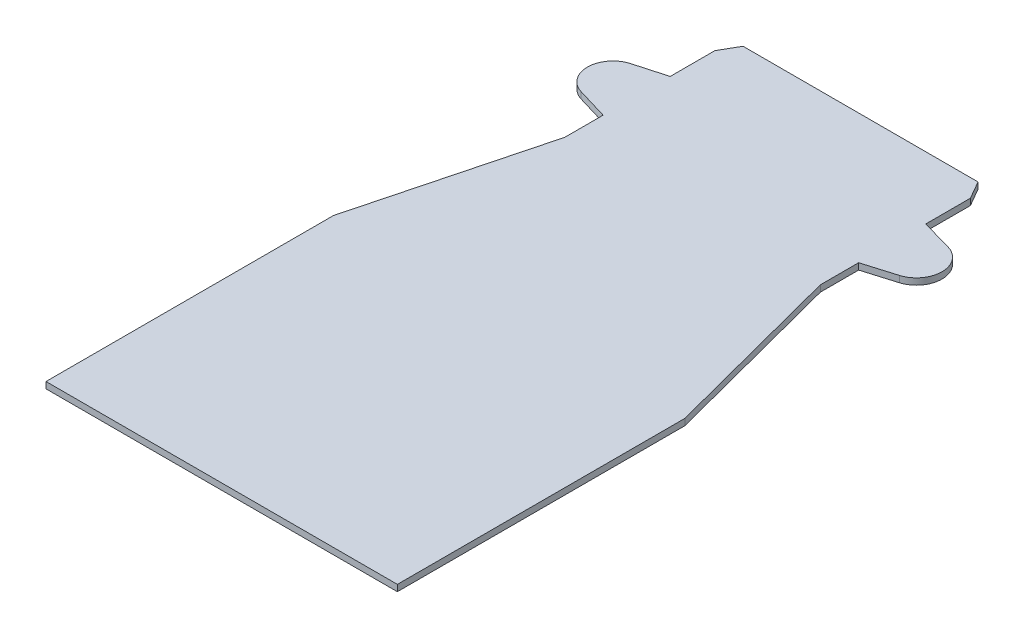
SolidWorks part; units mm, degrees
ref_plane "前视基准面" through (0, 0, 0) normal (0, 0, 1) x (1, 0, 0)
ref_plane "上视基准面" through (0, 0, 0) normal (0, 1, 0) x (1, 0, 0)
ref_plane "右视基准面" through (0, 0, 0) normal (1, 0, 0) x (0, 0, -1)
sketch "草图1" plane through (0, 0, 0) normal (0, 1, 0) x (1, 0, 0)
  line L0 (0, 0) -> (0, 262.6348) construction
  line L1 (55, 0) -> (-55, 0)
  line L2 (-55, 0) -> (-55, 90)
  line L3 (-55, 90) -> (-40, 147.4115)
  line L4 (-40, 147.4115) -> (-40, 159.4115)
  line L5 (-40, 159.4115) -> (-49.7889, 162.3344)
  line L6 (-49.6599, 177.7029) -> (-40, 180.4115)
  line L7 (-40, 180.4115) -> (-40, 194.4115)
  line L8 (-40, 194.4115) -> (-31, 210)
  line L9 (-31, 210) -> (31, 210)
  line L10 (40, 194.4115) -> (31, 210)
  line L11 (40, 180.4115) -> (40, 194.4115)
  line L12 (49.6599, 177.7029) -> (40, 180.4115)
  line L13 (40, 159.4115) -> (49.7889, 162.3344)
  line L14 (40, 147.4115) -> (40, 159.4115)
  line L15 (55, 90) -> (40, 147.4115)
  line L16 (55, 0) -> (55, 90)
  arc A0 (-49.7889, 162.3344) -> (-49.6599, 177.7029) centre (-47.5, 170) cw
  arc A1 (49.7889, 162.3344) -> (49.6599, 177.7029) centre (47.5, 170) ccw
  point P20 (0, 210)
  dimension "D11" = 8
  dimension "D2" = 90
  dimension "D3" = 110
  dimension "D4" = 62
  dimension "D5" = 80
  dimension "D6" = 80
  dimension "D7" = 40
  dimension "D8" = 210
  dimension "D9" = 14
  dimension "D10" = 12
  dimension "D12" = 21
  dimension "D13" = 120
  dimension "D14" = 95
extrude "凸台-拉伸1" add sketch "草图1" along normal mid plane 2
sketch "草图2" plane through (0, 0, -210) normal (0, 0, -1) x (-1, 0, 0)
  line L0 (40, -1) -> (49.6599, -1) construction
  line L1 (-44.8299, 1) -> (44.8299, 1)
  line L2 (-44.8299, 1) -> (-44.8299, -1)
  line L3 (-44.8299, -1) -> (44.8299, -1)
  line L4 (44.8299, 1) -> (44.8299, -1)
  line L5 (-44.8299, 1) -> (44.8299, -1) construction
  line L6 (-44.8299, -1) -> (44.8299, 1) construction
  point P0 (0, 0)
extrude "切除-拉伸1" cut sketch "草图2" against normal blind 10
